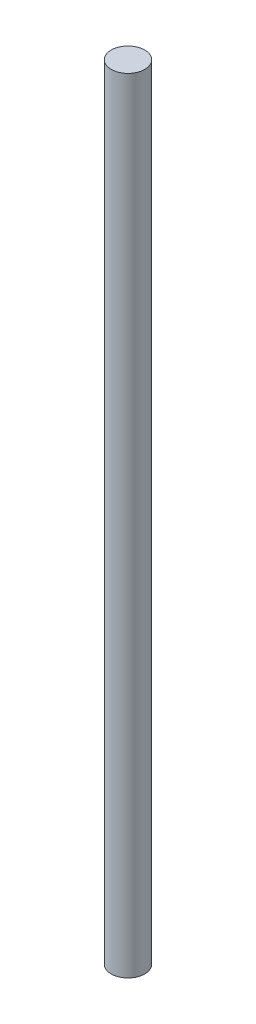
SolidWorks part; units mm, degrees
ref_plane "Front Plane" through (0, 0, 0) normal (0, 0, 1) x (1, 0, 0)
ref_plane "Top Plane" through (0, 0, 0) normal (0, 1, 0) x (1, 0, 0)
ref_plane "Right Plane" through (0, 0, 0) normal (1, 0, 0) x (0, 0, -1)
sketch "Sketch2" plane through (0, 0, 0) normal (0, 1, 0) x (1, 0, 0)
  circle A0 centre (0, 0) radius 3
  dimension "D1" = 6
extrude "Boss-Extrude1" add sketch "Sketch2" along normal blind 140
ref_plane "Plane1" through (0, 70, 0) normal (0, 1, 0) x (1, 0, 0)
